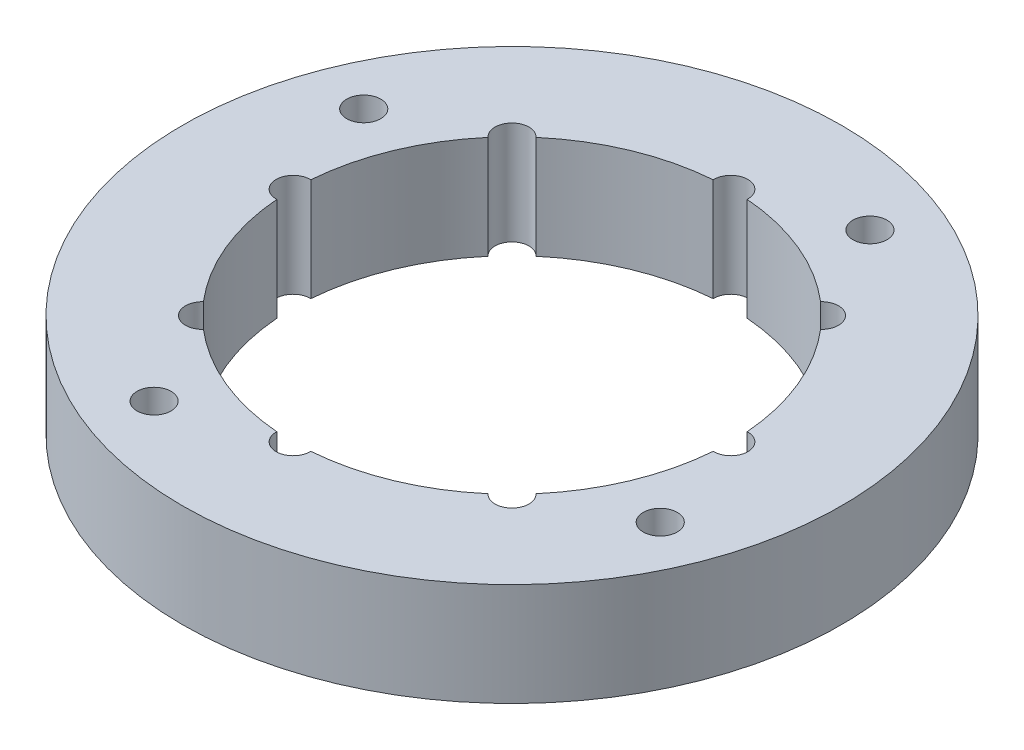
SolidWorks part; units mm, degrees
ref_plane "Front Plane" through (0, 0, 0) normal (0, 0, 1) x (1, 0, 0)
ref_plane "Top Plane" through (0, 0, 0) normal (0, 1, 0) x (1, 0, 0)
ref_plane "Right Plane" through (0, 0, 0) normal (1, 0, 0) x (0, 0, -1)
sketch "1.5in Socket" plane through (0, 0, 0) normal (0, 1, 0) x (1, 0, 0)
  line L0 (0, 0) -> (-19.083, 19.083) construction
  line L1 (0, 26.9875) -> (0, 0)
  line L2 (19.083, 19.083) -> (0, 0) construction
  line L3 (26.9875, 0) -> (0, 0)
  line L4 (19.083, -19.083) -> (0, 0) construction
  line L5 (0, -26.9875) -> (0, 0)
  line L6 (-19.083, -19.083) -> (0, 0) construction
  line L7 (-26.9875, 0) -> (0, 0) construction
  line L8 (-12.9278, -31.2105) -> (0, 0) construction
  line L9 (-31.2105, 12.9278) -> (0, 0) construction
  line L10 (31.2105, -12.9278) -> (0, 0) construction
  line L11 (12.9278, 31.2105) -> (0, 0) construction
  circle A0 centre (0, 0) radius 40.64
  arc A1 (-2.0939, 26.9061) -> (2.0939, 26.9061) centre (0, 26.9875) cw
  arc A2 (2.0939, 26.9061) -> (17.5449, 20.5061) centre (0, 0) cw
  arc A3 (17.5449, 20.5061) -> (20.5061, 17.5449) centre (19.083, 19.083) cw
  arc A4 (20.5061, 17.5449) -> (26.9061, 2.0939) centre (0, 0) cw
  arc A5 (26.9061, 2.0939) -> (26.9061, -2.0939) centre (26.9875, 0) cw
  arc A6 (26.9061, -2.0939) -> (20.5061, -17.5449) centre (0, 0) cw
  arc A7 (20.5061, -17.5449) -> (17.5449, -20.5061) centre (19.083, -19.083) cw
  arc A8 (17.5449, -20.5061) -> (2.0939, -26.9061) centre (0, 0) cw
  arc A9 (2.0939, -26.9061) -> (-2.0939, -26.9061) centre (0, -26.9875) cw
  arc A10 (-2.0939, -26.9061) -> (-17.5449, -20.5061) centre (0, 0) cw
  arc A11 (-17.5449, -20.5061) -> (-20.5061, -17.5449) centre (-19.083, -19.083) cw
  arc A12 (-20.5061, -17.5449) -> (-26.9061, -2.0939) centre (0, 0) cw
  arc A13 (-26.9061, -2.0939) -> (-26.9061, 2.0939) centre (-26.9875, 0) cw
  arc A14 (-26.9061, 2.0939) -> (-20.5061, 17.5449) centre (0, 0) cw
  arc A15 (-20.5061, 17.5449) -> (-17.5449, 20.5061) centre (-19.083, 19.083) cw
  arc A16 (-17.5449, 20.5061) -> (-2.0939, 26.9061) centre (0, 0) cw
  arc A18 (-2.0939, 26.9061) -> (-17.5449, 20.5061) centre (0, 0) ccw
  arc A19 (-17.5449, 20.5061) -> (-20.5061, 17.5449) centre (-19.083, 19.083) ccw
  arc A20 (-20.5061, 17.5449) -> (-26.9061, 2.0939) centre (0, 0) ccw
  arc A21 (-26.9061, 2.0939) -> (-26.9061, -2.0939) centre (-26.9875, 0) ccw
  arc A22 (-26.9061, -2.0939) -> (-20.5061, -17.5449) centre (0, 0) ccw
  arc A23 (-20.5061, -17.5449) -> (-17.5449, -20.5061) centre (-19.083, -19.083) ccw
  arc A24 (-17.5449, -20.5061) -> (-2.0939, -26.9061) centre (0, 0) ccw
  arc A25 (-2.0939, -26.9061) -> (2.0939, -26.9061) centre (0, -26.9875) ccw
  arc A26 (2.0939, -26.9061) -> (17.5449, -20.5061) centre (0, 0) ccw
  arc A27 (17.5449, -20.5061) -> (20.5061, -17.5449) centre (19.083, -19.083) ccw
  arc A28 (20.5061, -17.5449) -> (26.9061, -2.0939) centre (0, 0) ccw
  arc A29 (26.9061, -2.0939) -> (26.9061, 2.0939) centre (26.9875, 0) ccw
  arc A30 (26.9061, 2.0939) -> (20.5061, 17.5449) centre (0, 0) ccw
  arc A31 (20.5061, 17.5449) -> (17.5449, 20.5061) centre (19.083, 19.083) ccw
  arc A32 (17.5449, 20.5061) -> (2.0939, 26.9061) centre (0, 0) ccw
  arc A33 (2.0939, 26.9061) -> (-2.0939, 26.9061) centre (0, 26.9875) ccw
  circle A34 centre (-12.9278, -31.2105) radius 2.1
  circle A35 centre (-31.2105, 12.9278) radius 2.1
  circle A36 centre (31.2105, -12.9278) radius 2.1
  circle A37 centre (12.9278, 31.2105) radius 2.1
  point P27 (-19.083, -19.083)
  point P28 (-26.9875, 0)
  point P29 (0, 0)
  point P30 (0, -26.9875)
  point P31 (19.083, -19.083)
  point P32 (26.9875, 0)
  point P33 (19.083, 19.083)
  point P34 (0, 26.9875)
  point P35 (-19.083, 19.083)
  point P36 (0, 0)
  point P39 (47.4332, -12.4563)
  point P44 (0.7613, -0.7613)
  point P47 (0, 0)
  dimension "D1" = 2.0955
  dimension "D2" = 2.0955
  dimension "D3" = 2.0955
  dimension "D4" = 2.0955
  dimension "D5" = 2.0955
  dimension "D6" = 2.0955
  dimension "D7" = 2.0955
  dimension "D8" = 2.0955
  dimension "D9" = 26.9875
  dimension "D10" = 26.9875
  dimension "D11" = 26.9875
  dimension "D12" = 26.9875
  dimension "D13" = 26.9875
  dimension "D14" = 26.9875
  dimension "D15" = 26.9875
  dimension "D16" = 26.9875
  dimension "D17" = 81.28
  dimension "D26" = 4.2
  dimension "D28" = 33.782
  dimension "D30" = 4.2
  dimension "D31" = 4.2
  dimension "D32" = 4.2
  dimension "D18" = 26.9875
  dimension "D19" = 26.9875
  dimension "D20" = 26.9875
  dimension "D21" = 26.9875
  dimension "D22" = 26.9875
  dimension "D23" = 26.9875
  dimension "D24" = 26.9875
  dimension "D25" = 26.9875
  dimension "D27" = 33.782
  dimension "D29" = 90
  dimension "D33" = 90
  dimension "D34" = 90
  dimension "D35" = 33.782
  dimension "D36" = 33.782
  dimension "D37" = 67.5
extrude "Boss-Extrude1" add sketch "1.5in Socket" along normal blind 12.7 contours A0 A37 A36 A35 A34 A15 A16 A1 A2 A3 A4 A5 A6 A7 A8 A9 A10 A11 A12 A13 A14
